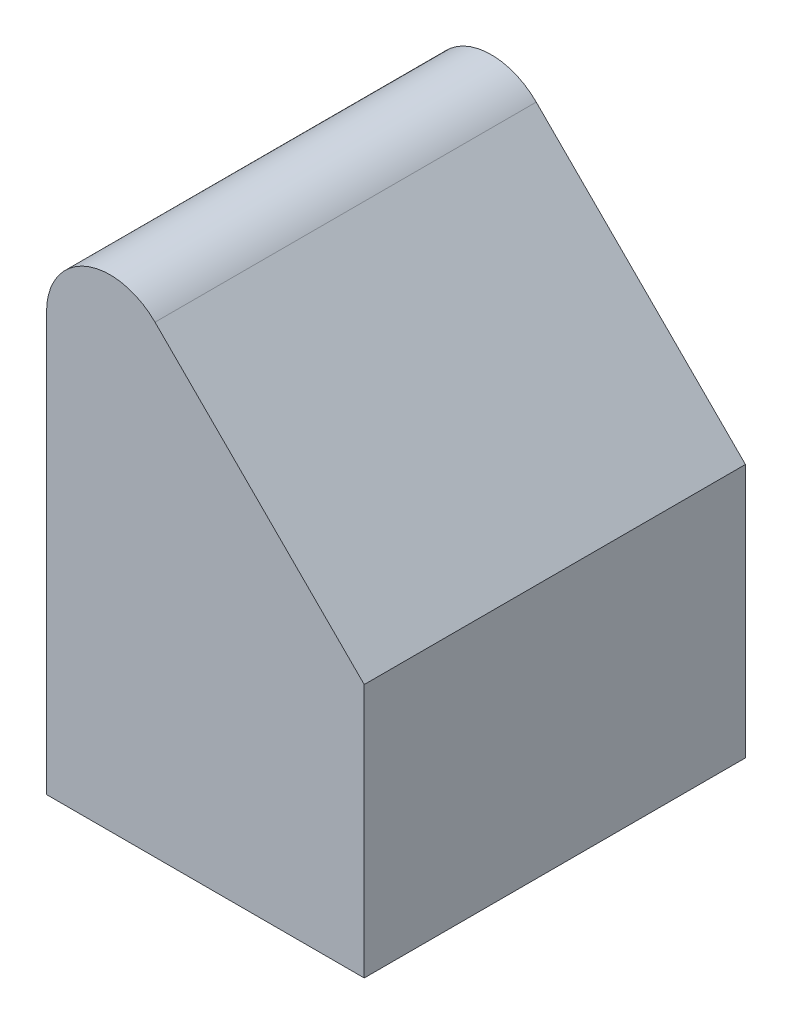
SolidWorks part; units mm, degrees
ref_plane "Alzado" through (0, 0, 0) normal (0, 0, 1) x (1, 0, 0)
ref_plane "Planta" through (0, 0, 0) normal (0, 1, 0) x (1, 0, 0)
ref_plane "Vista lateral" through (0, 0, 0) normal (1, 0, 0) x (0, 0, -1)
sketch "Croquis2" plane through (0, 0, 0) normal (1, 0, 0) x (0, 0, -1)
  line L0 (0, 0) -> (-30, 0)
  line L1 (0, 0) -> (-35.5397, 0) construction
  line L3 (0, -20) -> (-30, -20)
  line L7 (0, -20) -> (0, 0)
  line L8 (-30, -20) -> (-30, 0)
  line L10 (-35.5397, 0) -> (-75.7248, -24.1111) construction
  line L11 (-30, -20) -> (-55.7248, -35.4349) construction
  line L12 (-55.7248, -35.4349) -> (-55.7248, -45.4349) construction
  line L13 (-75.7248, -24.1111) -> (-75.7248, -45.4349) construction
  dimension "D1" = 30
  dimension "D4" = 20
extrude "Saliente-Extruir2" add sketch "Croquis2" along normal blind 25
sketch "Croquis3" plane through (0, 0, 0) normal (0, 0, -1) x (-1, 0, 0)
  line L0 (0, 0) -> (0, 25)
  line L1 (0, 25) -> (-25, 0)
  line L2 (-25, 0) -> (0, 0)
  dimension "D1" = 45
extrude "Saliente-Extruir3" add sketch "Croquis3" against normal through all
fillet "Redondeo1" radius 5 1 edges at (0, 25, 15)
